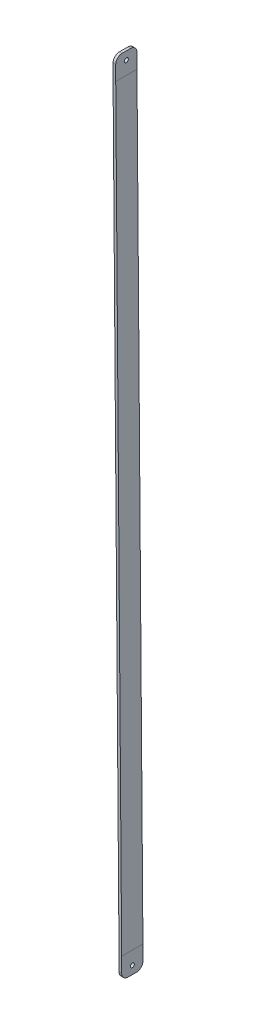
SolidWorks part; units mm, degrees
ref_plane "Front Plane" through (0, 0, 0) normal (0, 0, 1) x (1, 0, 0)
ref_plane "Top Plane" through (0, 0, 0) normal (0, 1, 0) x (1, 0, 0)
ref_plane "Right Plane" through (0, 0, 0) normal (1, 0, 0) x (0, 0, -1)
sketch "Sketch1" plane through (0, 0, 0) normal (0, 0, 1) x (1, 0, 0)
  line L0 (0, 0) -> (3.175, 0)
  line L1 (3.175, 0) -> (3.175, 25.4)
  line L2 (0, 0) -> (0, 25.4)
  line L3 (3.175, 25.4) -> (-3.937, 927.1)
  line L4 (0, 25.4) -> (-7.112, 927.1)
  line L5 (-3.937, 927.1) -> (-3.937, 952.5)
  line L6 (-7.112, 952.5) -> (-7.112, 927.1)
  line L7 (-7.112, 952.5) -> (-3.937, 952.5)
  point P9 (1.5875, 0)
  dimension "D1" = 25.4
  dimension "D2" = 3.175
  dimension "D3" = 25.4
  dimension "D4" = 7.112
  dimension "D5" = 25.4
  dimension "D6" = 25.4
  dimension "D7" = 952.5
extrude "Boss-Extrude1" add sketch "Sketch1" along normal mid plane 25.4
fillet "Fillet1" radius 7.62 4 edges at (1.5875, 0, 12.7) (1.5875, 0, -12.7) (-5.5245, 952.5, -12.7) (-5.5245, 952.5, 12.7)
sketch "Sketch2" plane through (-3.937, 0, 0) normal (1, 0, 0) x (0, 0, -1)
  line L0 (-5.08, 952.5) -> (5.08, 952.5) construction
  circle A0 centre (0, 942.848) radius 2.413
  circle A1 centre (0, 9.652) radius 2.413
  dimension "D1" = 4.826
  dimension "D2" = 4.826
  dimension "D3" = 9.652
  dimension "D4" = 933.196
extrude "Cut-Extrude1" cut sketch "Sketch2" against normal through all and the other way through all
